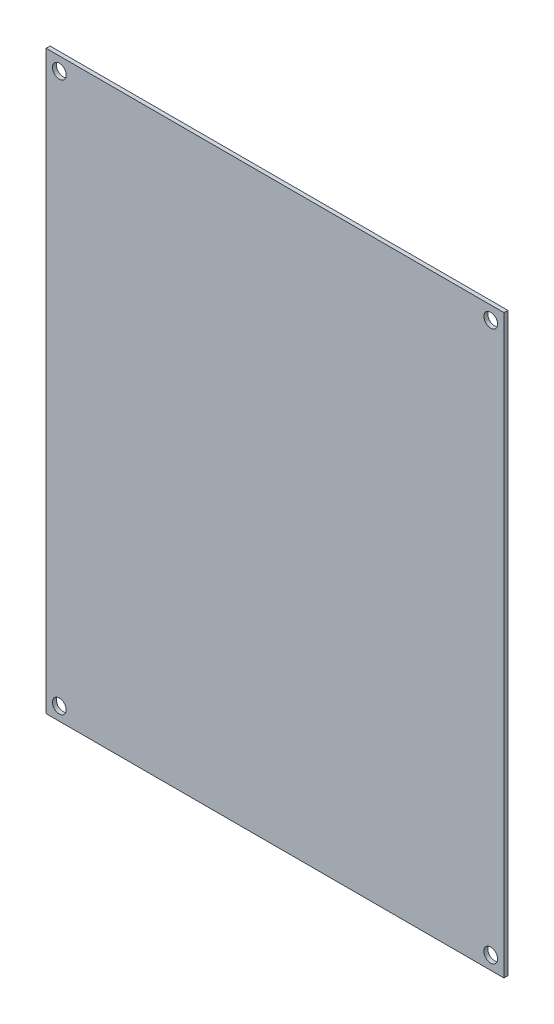
SolidWorks part; units mm, degrees
ref_plane "Front Plane" through (0, 0, 0) normal (0, 0, 1) x (1, 0, 0)
ref_plane "Top Plane" through (0, 0, 0) normal (0, 1, 0) x (1, 0, 0)
ref_plane "Right Plane" through (0, 0, 0) normal (1, 0, 0) x (0, 0, -1)
sketch "Sketch1" plane through (0, 0, 0) normal (0, 0, 1) x (1, 0, 0)
  line L0 (-54.65, 69.65) -> (-54.65, -69.65) construction
  line L1 (-58, 73) -> (58, 73)
  line L2 (-58, 73) -> (-58, -73)
  line L3 (-58, -73) -> (58, -73)
  line L4 (58, 73) -> (58, -73)
  line L5 (-58, 73) -> (58, -73) construction
  line L6 (-58, -73) -> (58, 73) construction
  line L7 (-54.65, -69.65) -> (54.65, -69.65) construction
  line L8 (54.65, -69.65) -> (54.65, 69.65) construction
  line L9 (54.65, 69.65) -> (-54.65, 69.65) construction
  line L10 (0, 69.65) -> (0, -69.65) construction
  circle A0 centre (-54.65, 69.65) radius 1.75
  circle A1 centre (54.65, 69.65) radius 1.75
  circle A2 centre (54.65, -69.65) radius 1.75
  circle A3 centre (-54.65, -69.65) radius 1.75
  point P0 (0, 0)
  point P13 (0, 0)
  point P17 (0, 0)
  dimension "D1" = 3.5
  dimension "D2" = 116
  dimension "D3" = 146
  dimension "D4" = 3.35
  dimension "D5" = 3.35
extrude "Boss-Extrude1" add sketch "Sketch1" along normal blind 1
